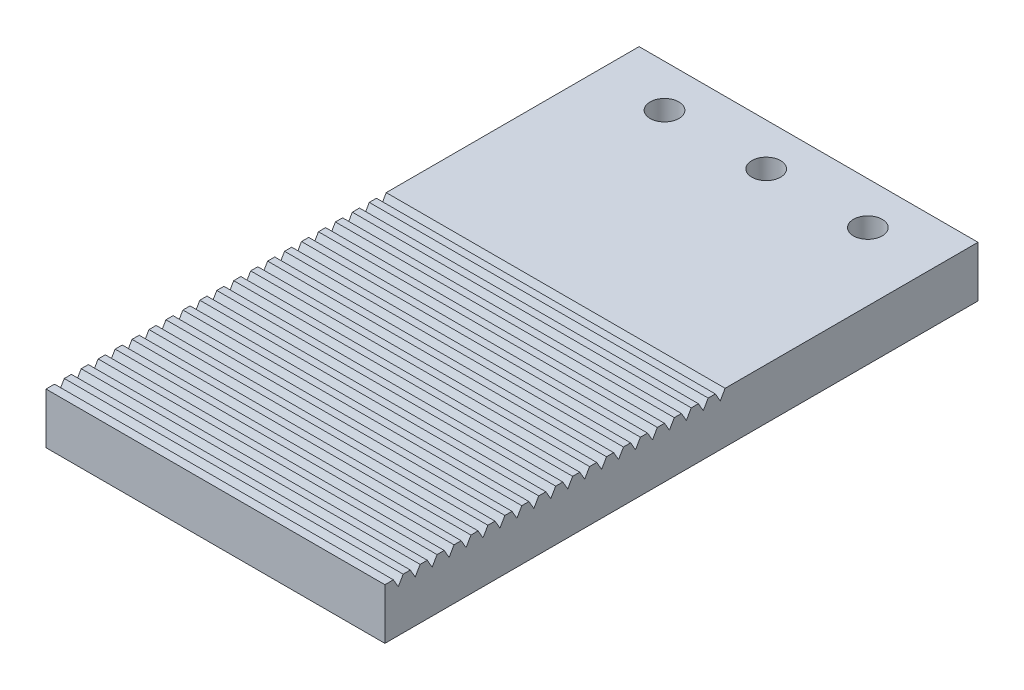
SolidWorks part; units mm, degrees
ref_plane "Front" through (0, 0, 0) normal (0, 0, 1) x (1, 0, 0)
ref_plane "Top" through (0, 0, 0) normal (0, 1, 0) x (1, 0, 0)
ref_plane "Right" through (0, 0, 0) normal (1, 0, 0) x (0, 0, -1)
sketch "草图1" plane through (0, 0, 0) normal (0, 1, 0) x (1, 0, 0)
  line L1 (-20, 35) -> (20, 35)
  line L2 (-20, 35) -> (-20, -35)
  line L3 (-20, -35) -> (20, -35)
  line L4 (20, 35) -> (20, -35)
  line L5 (-20, 35) -> (20, -35) construction
  line L6 (-20, -35) -> (20, 35) construction
  point P0 (0, 0)
  dimension "D1" = 40
  dimension "D2" = 70
extrude "凸台-拉伸1" add sketch "草图1" along normal blind 6
sketch "草图4" plane through (20, 0, 0) normal (1, 0, 0) x (0, 0, -1)
  line L0 (-34, 6) -> (-33.4226, 5)
  line L1 (-35, 6) -> (35, 6) construction
  line L2 (-33.4226, 5) -> (-32.8453, 6)
  line L3 (-34, 6) -> (-32.8453, 6)
  line L4 (-32, 6) -> (-30.8453, 6)
  line L5 (-32, 6) -> (-31.4226, 5)
  line L6 (-31.4226, 5) -> (-30.8453, 6)
  line L7 (-30, 6) -> (-28.8453, 6)
  line L8 (-30, 6) -> (-29.4226, 5)
  line L9 (-29.4226, 5) -> (-28.8453, 6)
  line L10 (-28, 6) -> (-26.8453, 6)
  line L11 (-28, 6) -> (-27.4226, 5)
  line L12 (-27.4226, 5) -> (-26.8453, 6)
  line L13 (-26, 6) -> (-24.8453, 6)
  line L14 (-26, 6) -> (-25.4226, 5)
  line L15 (-25.4226, 5) -> (-24.8453, 6)
  line L16 (-24, 6) -> (-22.8453, 6)
  line L17 (-24, 6) -> (-23.4226, 5)
  line L18 (-23.4226, 5) -> (-22.8453, 6)
  line L19 (-22, 6) -> (-20.8453, 6)
  line L20 (-22, 6) -> (-21.4226, 5)
  line L21 (-21.4226, 5) -> (-20.8453, 6)
  line L22 (-20, 6) -> (-18.8453, 6)
  line L23 (-20, 6) -> (-19.4226, 5)
  line L24 (-19.4226, 5) -> (-18.8453, 6)
  line L25 (-18, 6) -> (-16.8453, 6)
  line L26 (-18, 6) -> (-17.4226, 5)
  line L27 (-17.4226, 5) -> (-16.8453, 6)
  line L28 (-16, 6) -> (-14.8453, 6)
  line L29 (-16, 6) -> (-15.4226, 5)
  line L30 (-15.4226, 5) -> (-14.8453, 6)
  line L31 (-14, 6) -> (-12.8453, 6)
  line L32 (-14, 6) -> (-13.4226, 5)
  line L33 (-13.4226, 5) -> (-12.8453, 6)
  line L34 (-12, 6) -> (-10.8453, 6)
  line L35 (-12, 6) -> (-11.4226, 5)
  line L36 (-11.4226, 5) -> (-10.8453, 6)
  line L37 (-10, 6) -> (-8.8453, 6)
  line L38 (-10, 6) -> (-9.4226, 5)
  line L39 (-9.4226, 5) -> (-8.8453, 6)
  line L40 (-8, 6) -> (-6.8453, 6)
  line L41 (-8, 6) -> (-7.4226, 5)
  line L42 (-7.4226, 5) -> (-6.8453, 6)
  line L43 (-6, 6) -> (-4.8453, 6)
  line L44 (-6, 6) -> (-5.4226, 5)
  line L45 (-5.4226, 5) -> (-4.8453, 6)
  line L46 (-4, 6) -> (-2.8453, 6)
  line L47 (-4, 6) -> (-3.4226, 5)
  line L48 (-3.4226, 5) -> (-2.8453, 6)
  line L49 (-2, 6) -> (-0.8453, 6)
  line L50 (-2, 6) -> (-1.4226, 5)
  line L51 (-1.4226, 5) -> (-0.8453, 6)
  line L52 (0, 6) -> (1.1547, 6)
  line L53 (0, 6) -> (0.5774, 5)
  line L54 (0.5774, 5) -> (1.1547, 6)
  line L55 (2, 6) -> (3.1547, 6)
  line L56 (2, 6) -> (2.5774, 5)
  line L57 (2.5774, 5) -> (3.1547, 6)
  line L58 (4, 6) -> (5.1547, 6)
  line L59 (4, 6) -> (4.5774, 5)
  line L60 (4.5774, 5) -> (5.1547, 6)
  dimension "D1" = 1
  dimension "D2" = 60
  dimension "D3" = 60
  dimension "D4" = 1
  dimension "D5" = 20
extrude "切除-拉伸1" cut sketch "草图4" against normal through all
sketch "草图5" plane through (0, 0, 0) normal (0, -1, 0) x (1, 0, 0)
  line L0 (-35.7117, -30) -> (34.7292, -30) construction
  line L1 (0, 0) -> (0, -51.4593) construction
  line L2 (20, -35) -> (-20, -35) construction
  point P7 (0, -30)
  point P8 (-12, -30)
  point P9 (0, 0)
  point P10 (12, -30)
  dimension "D1" = 5
  dimension "D2" = 12
hole_wizard "打孔尺寸(%根据)内六角圆柱头螺钉的类型2" positions "3D草图2" profile "草图6" counterbore size "M3" standard "GB" end condition through all
sketch3d "3D草图2"
  point P0 (-12, 0, -30)
  point P3 (0, 0, -30)
  point P6 (12, 0, -30)
sketch "草图6" plane through (-12, 0, -30) normal (1, 0, 0) x (0, 0, -1)
  line L0 (0, 0) -> (0, 6)
  line L1 (0, 6) -> (1.7, 6)
  line L3 (1.7, 6) -> (1.7, 3.4)
  line L4 (1.7, 3.4) -> (3, 3.4)
  line L5 (3, 3.4) -> (3, 0)
  line L7 (3, 0) -> (0, 0)
  line L11 (0, -6.35) -> (0, 107.95) construction
  dimension "通孔孔直径" = 3.4
  dimension "通孔孔深度" = 6
  dimension "柱形沉头孔直径" = 6
  dimension "柱形沉头孔深度" = 3.4
